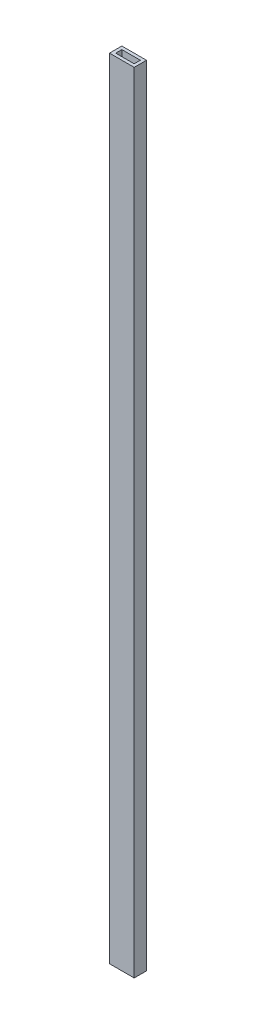
SolidWorks part; units mm, degrees
ref_plane "Front Plane" through (0, 0, 0) normal (0, 0, 1) x (1, 0, 0)
ref_plane "Top Plane" through (0, 0, 0) normal (0, 1, 0) x (1, 0, 0)
ref_plane "Right Plane" through (0, 0, 0) normal (1, 0, 0) x (0, 0, -1)
sketch "Sketch1" plane through (0, 0, 0) normal (0, 1, 0) x (1, 0, 0)
  line L1 (0, 0) -> (25.4, 0)
  line L2 (0, 0) -> (0, 12.7)
  line L3 (0, 12.7) -> (25.4, 12.7)
  line L4 (25.4, 0) -> (25.4, 12.7)
  dimension "D1" = 12.7
  dimension "D2" = 25.4
extrude "Extrude-Thin1" add sketch "Sketch1" along normal blind 812.8 thin thin type one direction reverse wall 3.175
